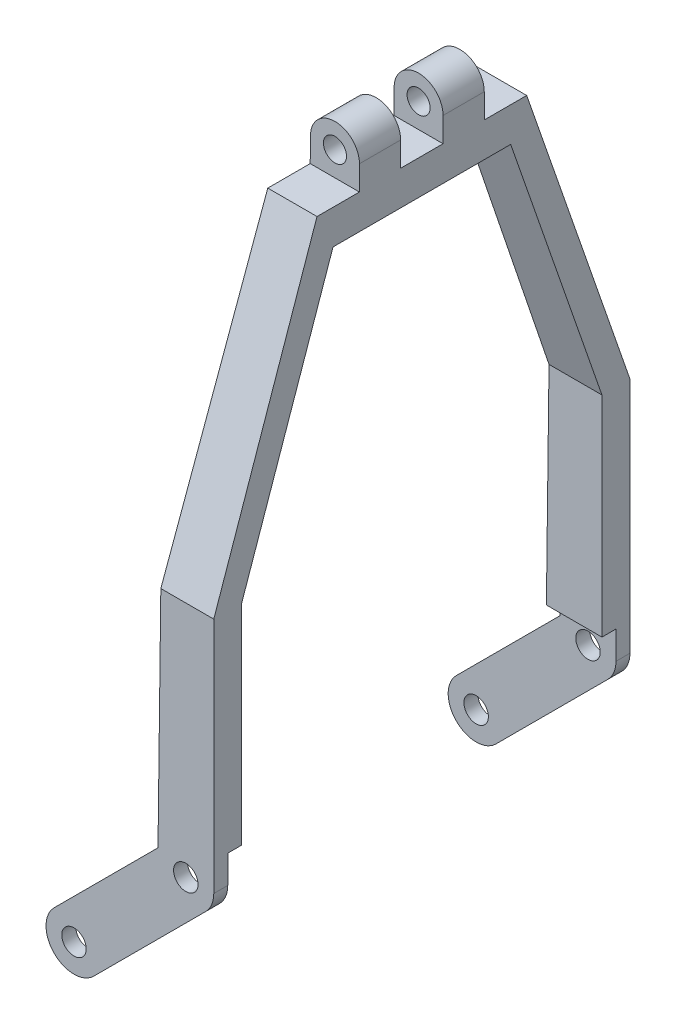
SolidWorks part; units mm, degrees
ref_plane "Front Plane" through (0, 0, 0) normal (0, 0, 1) x (1, 0, 0)
ref_plane "Top Plane" through (0, 0, 0) normal (0, 1, 0) x (1, 0, 0)
ref_plane "Right Plane" through (0, 0, 0) normal (1, 0, 0) x (0, 0, -1)
sketch "Croquis1" plane through (0, 0, 0) normal (0, 0, 1) x (1, 0, 0)
  line L0 (-13.1716, -18.8284) -> (2.8284, -2.8284)
  line L5 (-3.9793, 1.6775) -> (-18.8284, -13.1716)
  line L10 (-2.9997, 80.0422) -> (-3.9793, 1.6775)
  line L11 (4, 0) -> (4, 79.9984)
  circle A18 centre (0, 0) radius 1.75
  circle A19 centre (-16, -16) radius 1.75
  arc A20 (-18.8284, -13.1716) -> (-13.1716, -18.8284) centre (-16, -16) ccw
  arc A21 (2.8284, -2.8284) -> (4, 0) centre (0, 0) ccw
  arc A22 (4, 79.9984) -> (-2.9997, 80.0422) centre (0.5, 79.9984) ccw
  circle A23 centre (0.5, 79.9984) radius 1.65
  dimension "D3" = 3.5
  dimension "D4" = 8
  dimension "D6" = 7
  dimension "D7" = 3.3
  dimension "D1" = 16
  dimension "D2" = 16
  dimension "D5" = 80
extrude "Saliente-Extruir1" add sketch "Croquis1" against normal blind 59.54
sketch "Croquis2" plane through (4, 0, 0) normal (1, 0, 0) x (0, 0, -1)
  line L0 (0, -20) -> (59.54, -20) construction
  line L1 (2, -20) -> (57.54, -20)
  line L2 (2, -20) -> (2, 4)
  line L3 (2, 4) -> (57.54, 4)
  line L4 (57.54, -20) -> (57.54, 4)
  line L5 (59.54, 0) -> (0, 0) construction
  line L6 (14.77, 83.4984) -> (0, 83.4984)
  line L7 (0, 0) -> (0, 79.9984) construction
  line L8 (4, 4) -> (55.54, 4)
  line L9 (4, 4) -> (4, 34)
  line L10 (4, 34) -> (55.54, 34)
  line L11 (55.54, 4) -> (55.54, 34)
  line L12 (59.54, 0) -> (59.54, 79.9984) construction
  line L13 (29.77, 83.4984) -> (29.77, 34) construction
  line L14 (55.54, 34) -> (42.4795, 71.5796)
  line L15 (0, 83.4984) -> (0, 34)
  line L16 (59.54, 83.4984) -> (0, 83.4984) construction
  line L17 (59.54, 79.9984) -> (0, 79.9984) construction
  line L18 (59.54, 34) -> (59.54, 83.4984)
  line L19 (59.54, 79.9984) -> (59.54, 83.4984) construction
  line L20 (59.54, 83.4984) -> (44.77, 83.4984)
  line L21 (44.77, 83.4984) -> (44.77, 76.4984)
  line L22 (44.77, 76.4984) -> (59.54, 34)
  line L23 (0, 34) -> (14.77, 76.4984)
  line L24 (14.77, 76.4984) -> (14.77, 83.4984)
  line L25 (0, 83.4984) -> (0, 79.9984) construction
  line L26 (4, 34) -> (17.0605, 71.5796)
  line L27 (17.0605, 71.5796) -> (42.4795, 71.5796)
  line L29 (14.77, 83.4984) -> (20.84, 83.4984)
  line L30 (14.77, 83.4984) -> (14.77, 76.4984)
  line L31 (14.77, 76.4984) -> (20.84, 76.4984)
  line L32 (20.84, 83.4984) -> (20.84, 76.4984)
  line L33 (44.77, 76.4984) -> (38.7, 76.4984)
  line L34 (44.77, 76.4984) -> (44.77, 83.4984)
  line L35 (44.77, 83.4984) -> (38.7, 83.4984)
  line L36 (38.7, 76.4984) -> (38.7, 83.4984)
  line L37 (32.805, 83.4984) -> (26.735, 83.4984)
  line L38 (32.805, 83.4984) -> (32.805, 76.4984)
  line L39 (32.805, 76.4984) -> (26.735, 76.4984)
  line L40 (26.735, 83.4984) -> (26.735, 76.4984)
  point P9 (29.77, 0)
  point P10 (29.77, 4)
  point P24 (29.77, 79.9984)
  point P48 (28.5269, 83.4984)
  point P49 (0, 0)
  point P50 (29.77, 83.4984)
  point P51 (0, 0)
  line M32 (0, 79.9984) -> (0, 0)
  line M33 (0, 0) -> (59.54, 0)
  line M34 (59.54, 0) -> (59.54, 79.9984)
  line M35 (59.54, 79.9984) -> (0, 79.9984)
  dimension "D1" = 55.54
  dimension "D2" = 30
  dimension "D3" = 4
  dimension "D4" = 4
  dimension "D5" = 15
  dimension "D6" = 7
  dimension "D7" = 4.9189
  dimension "D8" = 7
  dimension "D9" = 15
  dimension "D10" = 6.07
  dimension "D11" = 4
extrude "Cortar-Extruir1" cut sketch "Croquis2" against normal through all contours L32 L29 L24 M35 | L32 L24 L31 M35 | L36 L21 L35 M35 | L36 L33 L21 M35 | L20 L21 L18 M35 | L24 L6 L15 M35 | L23 L24 M35 M32 | L21 L22 M34 M35 | L3 L11 L10 L9 | L1 L4 L3 L2 M33 | L13 L27 L26 L10 | L27 L13 L10 L14 | L4 L3 L2 M33 | L39 L40 L37 L38
